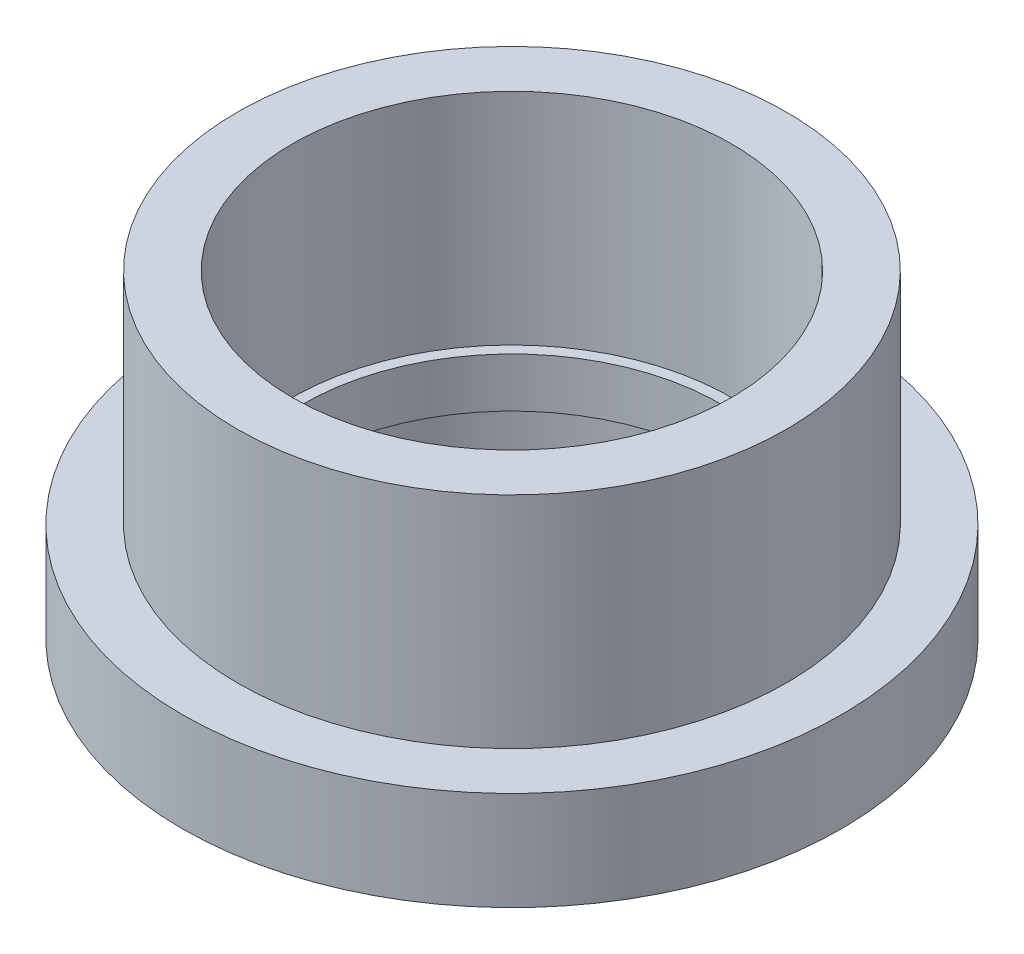
SolidWorks part; units mm, degrees
ref_plane "Front Plane" through (0, 0, 0) normal (0, 0, 1) x (1, 0, 0)
ref_plane "Top Plane" through (0, 0, 0) normal (0, 1, 0) x (1, 0, 0)
ref_plane "Right Plane" through (0, 0, 0) normal (1, 0, 0) x (0, 0, -1)
sketch "Sketch1" plane through (0, 0, 0) normal (0, 0, 1) x (1, 0, 0)
  line L0 (38, 0) -> (38, 9)
  line L1 (0, 83.5208) -> (0, -98.2024) construction
  line L2 (38, 9) -> (60, 9)
  line L3 (60, 9) -> (60, -9)
  line L4 (60, -9) -> (40.25, -9)
  line L5 (40.25, -9) -> (40.25, 0)
  line L6 (40.25, 0) -> (38, 0)
  dimension "D1" = 38
  dimension "D2" = 60
  dimension "D3" = 40.25
  dimension "D4" = 18
  dimension "D5" = 9
  dimension "D6" = 0
revolve "Revolve1" add sketch "Sketch1" angle 360 about L1
sketch "Sketch3" plane through (0, -9, 0) normal (0, -1, 0) x (1, 0, 0)
  circle A0 centre (0, 45.125) radius 1.6
  circle A1 centre (45.125, 0) radius 1.6
  circle A2 centre (0, -45.125) radius 1.6
  circle A3 centre (-45.125, 0) radius 1.6
  point P12 (0, 0)
  dimension "D1" = 3.2
  dimension "D2" = 45.125
  dimension "D3" = 4
extrude "Cut-Extrude1" cut sketch "Sketch3" against normal blind 10
sketch "Sketch4" plane through (0, 9, 0) normal (0, 1, 0) x (1, 0, 0)
  circle A0 centre (0, 0) radius 40
  circle A1 centre (0, 0) radius 50
  dimension "D1" = 80
  dimension "D2" = 100
extrude "Boss-Extrude1" add sketch "Sketch4" along normal blind 40
